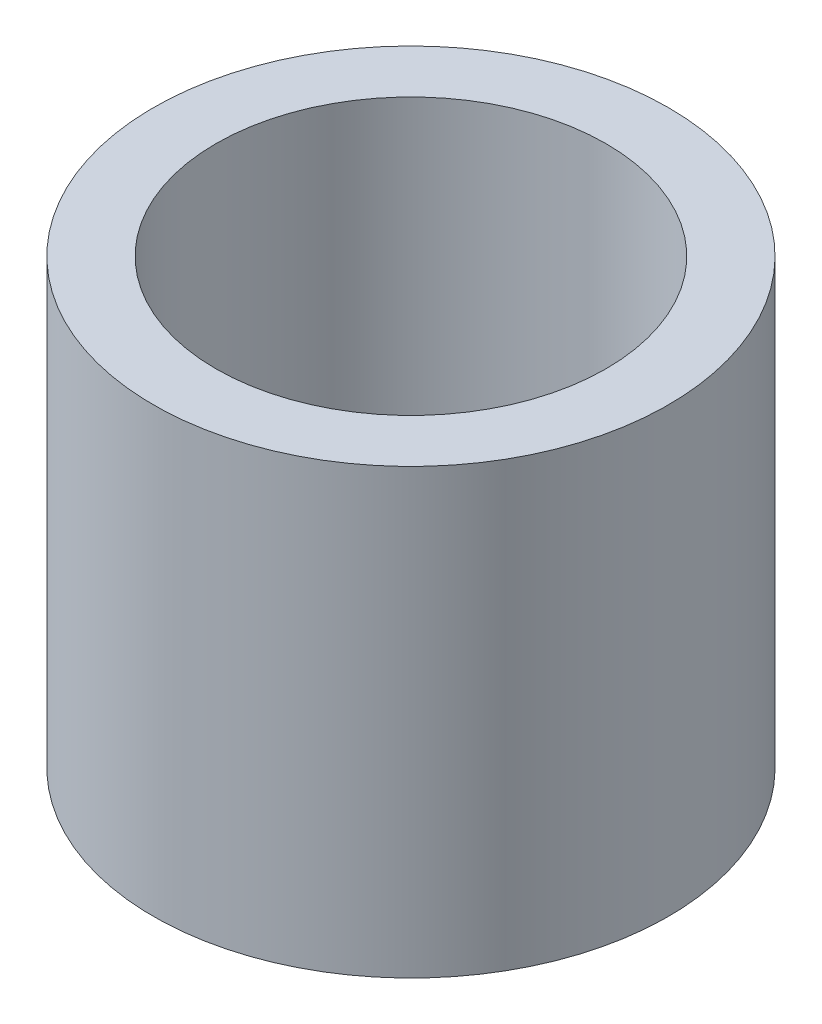
SolidWorks part; units mm, degrees
ref_plane "Спереди" through (0, 0, 0) normal (0, 0, 1) x (1, 0, 0)
ref_plane "Сверху" through (0, 0, 0) normal (0, 1, 0) x (1, 0, 0)
ref_plane "Справа" through (0, 0, 0) normal (1, 0, 0) x (0, 0, -1)
sketch "Эскиз1" plane through (0, 0, 0) normal (0, 0, 1) x (1, 0, 0)
  line L0 (0, 0) -> (0, 4380.1832) construction
  line L1 (-2.5, 0) -> (-2.5, 2)
  line L2 (-2.5, 2) -> (-6.25, 2)
  line L3 (-6.25, 2) -> (-6.25, 14.1975)
  line L4 (-6.25, 14.1975) -> (-8.25, 14.1975)
  line L5 (-8.25, 14.1975) -> (-8.25, 0)
  line L6 (-8.25, 0) -> (-2.5, 0)
  point P7 (0, 0)
  dimension "D1" = 5
  dimension "D2" = 2
  dimension "D3" = 2
  dimension "D4" = 12.5
revolve "Повернуть1" add sketch "Эскиз1" angle 360 about L0
